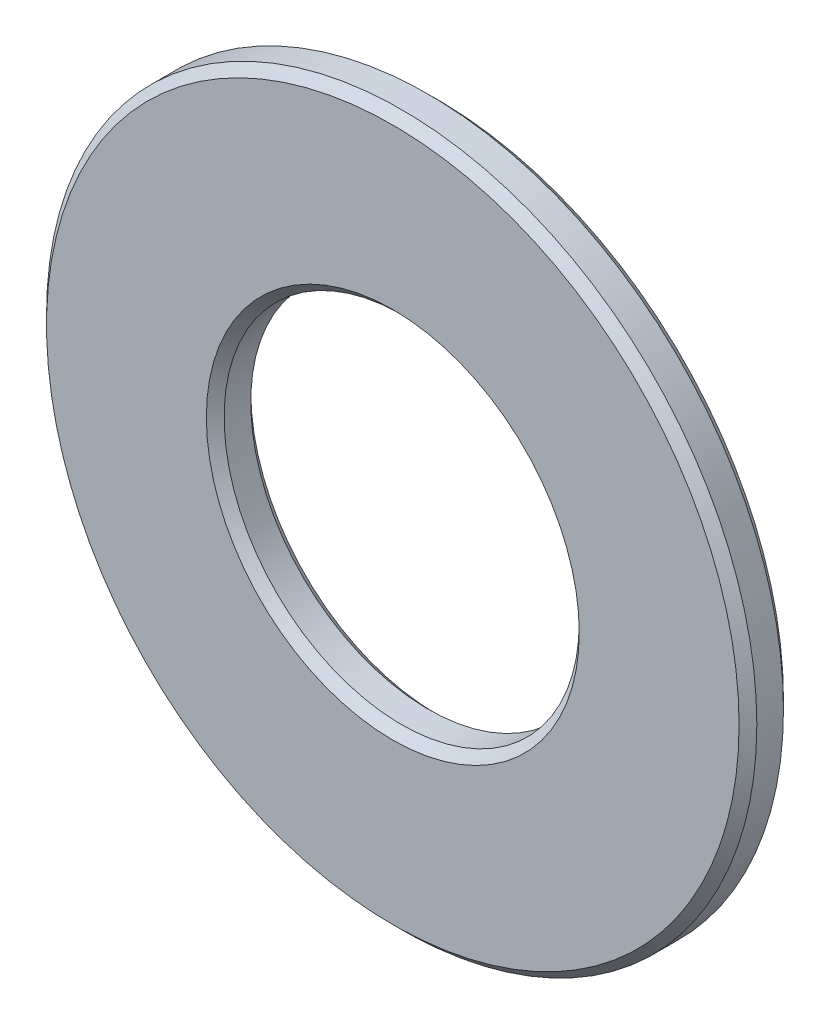
SolidWorks part; units mm, degrees
ref_plane "前视基准面" through (0, 0, 0) normal (0, 0, 1) x (1, 0, 0)
ref_plane "上视基准面" through (0, 0, 0) normal (0, 1, 0) x (1, 0, 0)
ref_plane "右视基准面" through (0, 0, 0) normal (1, 0, 0) x (0, 0, -1)
sketch "草图1" plane through (0, 0, 0) normal (0, 0, 1) x (1, 0, 0)
  circle A0 centre (0, 0) radius 2
  circle A1 centre (0, 0) radius 4
  dimension "D1" = 4
  dimension "D2" = 8
extrude "凸台-拉伸1" add sketch "草图1" along normal mid plane 0.5
chamfer "倒角1" distance 0.1 angle 45 4 edges at (2, 0, 0.25) (2, 0, -0.25) (4, 0, -0.25) (4, 0, 0.25)
